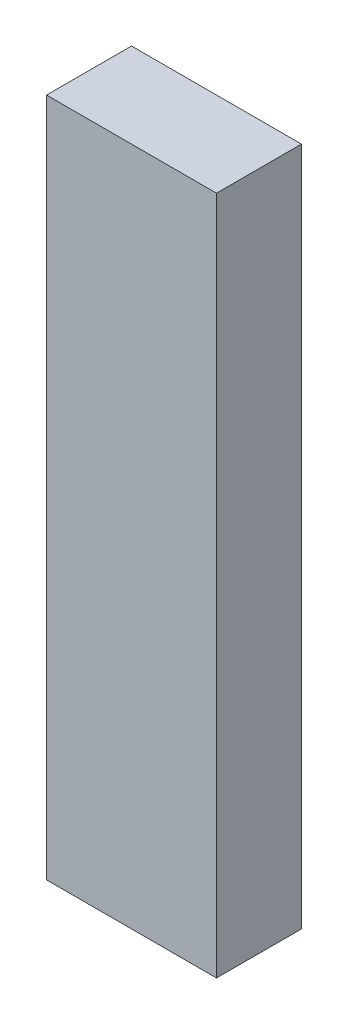
SolidWorks part; units mm, degrees
ref_plane "Front Plane" through (0, 0, 0) normal (0, 0, 1) x (1, 0, 0)
ref_plane "Top Plane" through (0, 0, 0) normal (0, 1, 0) x (1, 0, 0)
ref_plane "Right Plane" through (0, 0, 0) normal (1, 0, 0) x (0, 0, -1)
sketch "Sketch1" plane through (0, 0, 0) normal (0, 1, 0) x (1, 0, 0)
  line L1 (0, 0) -> (25.4, 0)
  line L2 (0, 0) -> (0, 12.7)
  line L3 (0, 12.7) -> (25.4, 12.7)
  line L4 (25.4, 0) -> (25.4, 12.7)
  dimension "D1" = 25.4
  dimension "D2" = 12.7
extrude "Boss-Extrude1" add sketch "Sketch1" along normal blind 101.6
